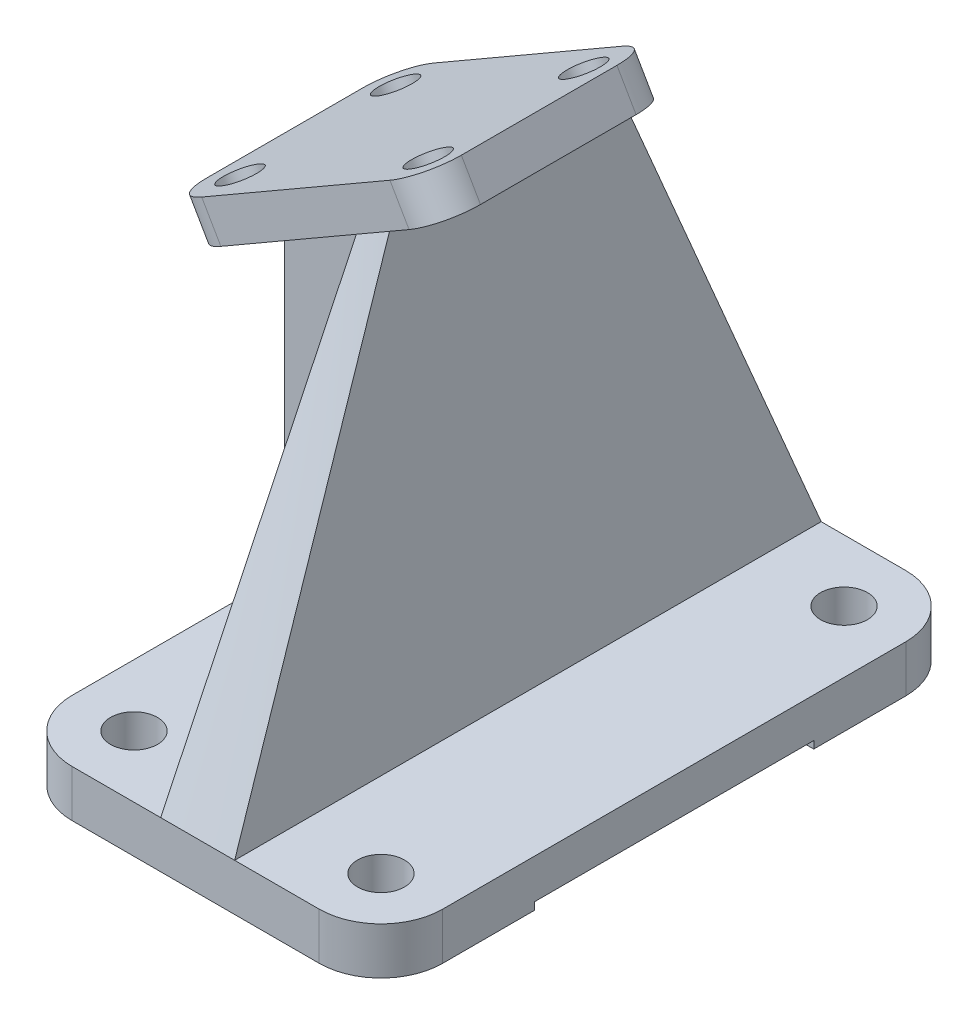
SolidWorks part; units mm, degrees
material "PA Type 6"
ref_plane "Front Plane" through (0, 0, 0) normal (0, 0, 1) x (1, 0, 0)
ref_plane "Top Plane" through (0, 0, 0) normal (0, 1, 0) x (1, 0, 0)
ref_plane "Right Plane" through (0, 0, 0) normal (1, 0, 0) x (0, 0, -1)
sketch "Sketch1" plane through (0, 0, 0) normal (0, 1, 0) x (1, 0, 0)
  line L1 (-25.4, 60.325) -> (25.4, 60.325)
  line L2 (-38.1, 47.625) -> (-38.1, -47.625)
  line L3 (-25.4, -60.325) -> (25.4, -60.325)
  line L4 (38.1, 47.625) -> (38.1, -47.625)
  arc A0 (-25.4, 60.325) -> (-38.1, 47.625) centre (-25.4, 47.625) ccw
  arc A1 (25.4, 60.325) -> (38.1, 47.625) centre (25.4, 47.625) cw
  arc A2 (25.4, -60.325) -> (38.1, -47.625) centre (25.4, -47.625) ccw
  arc A3 (-38.1, -47.625) -> (-25.4, -60.325) centre (-25.4, -47.625) ccw
  circle A4 centre (-25.4, -47.625) radius 4.826
  circle A5 centre (25.4, -47.625) radius 4.826
  circle A6 centre (25.4, 47.625) radius 4.826
  circle A7 centre (-25.4, 47.625) radius 4.826
  point P0 (0, 0)
  point P1 (0, 0)
  point P2 (0, -60.325)
  point P3 (38.1, 0)
  point P22 (0, 0)
  point P23 (0, 0)
  dimension "D3" = 12.7
  dimension "D4" = 9.652
  dimension "D1" = 95.25
  dimension "D2" = 76.2
extrude "Boss-Extrude1" add sketch "Sketch1" along normal blind 9.652
sketch "Sketch2" plane through (-38.1, 0, 0) normal (-1, 0, 0) x (0, 0, 1)
  line L1 (-28.702, 1.524) -> (28.702, 1.524)
  line L2 (-28.702, 1.524) -> (-28.702, -1.524)
  line L3 (-28.702, -1.524) -> (28.702, -1.524)
  line L4 (28.702, 1.524) -> (28.702, -1.524)
  line L5 (-28.702, 1.524) -> (28.702, -1.524) construction
  line L6 (-28.702, -1.524) -> (28.702, 1.524) construction
  point P0 (0, 0)
  point P6 (0, 0)
  point P7 (28.702, 0)
  dimension "D1" = 3.048
  dimension "D2" = 57.404
extrude "Cut-Extrude1" cut sketch "Sketch2" against normal through all
sketch "Sketch3" plane through (0, 9.652, 0) normal (0, 1, 0) x (1, 0, 0)
  line L0 (0, 60.325) -> (0, -60.325) construction
  line L1 (25.4, 60.325) -> (-25.4, 60.325) construction
  line L2 (-25.4, -60.325) -> (25.4, -60.325) construction
  line L3 (-38.1, 47.625) -> (-38.1, -47.625) construction
  line L4 (8.0051, 60.325) -> (-7.2117, 60.325)
  line L5 (8.0051, 60.325) -> (8.0051, -60.325)
  line L6 (8.0051, -60.325) -> (-7.2117, -60.325)
  line L7 (-7.2117, 60.325) -> (-7.2117, -60.325)
  circle A0 centre (-25.4, -47.625) radius 4.826 construction
  point P12 (0, 0)
  point P14 (-33.4581, -42.6977)
  dimension "D2" = 25.4
  dimension "D1" = 17.526
sketch "Sketch4" plane through (0, 0, 0) normal (0, 0, 1) x (1, 0, 0)
  line L0 (-38.1, 9.652) -> (-38.1, 77.216) construction
  line L1 (-38.1, 77.216) -> (4.1761, 101.6241) construction
  point P2 (0, 0)
  point P5 (0, 0)
  dimension "D1" = 67.564
  dimension "D2" = 120
ref_plane "Plane1" through (-42.9605, 74.4098, 0) normal (0.5, -0.866, 0) x (0.866, 0.5, 0)
sketch "Sketch5" plane through (-42.9605, 74.4098, 0) normal (0.5, -0.866, 0) x (0.866, 0.5, 0)
  line L1 (5.6124, -23.876) -> (66.0644, -23.876)
  line L2 (5.6124, -23.876) -> (5.6124, 23.876)
  line L3 (5.6124, 23.876) -> (66.0644, 23.876)
  line L4 (66.0644, -23.876) -> (66.0644, 23.876)
  line L5 (5.6124, 0) -> (66.0644, 0) construction
  line L7 (5.6124, 0) -> (54.4286, 0) construction
  point P7 (0, 0)
  point P8 (5.6124, 0)
  dimension "D1" = 60.452
  dimension "D2" = 47.752
extrude "Boss-Extrude2" add sketch "Sketch5" against normal blind 7.874 separate body
fillet "Fillet1" radius 7.874 4 edges at (-40.0685, 80.6255, -23.876) (12.2845, 110.8515, -23.876) (12.2845, 110.8515, 23.876) (-40.0685, 80.6255, 23.876)
sketch "Sketch7" plane through (-46.8975, 81.2289, 0) normal (-0.5, 0.866, 0) x (0.866, 0.5, 0)
  circle A0 centre (13.4864, 16.002) radius 3.937
  circle A1 centre (13.4864, -16.002) radius 3.937
  circle A2 centre (58.1904, -16.002) radius 3.937
  circle A3 centre (58.1904, 16.002) radius 3.937
  dimension "D1" = 7.874
extrude "Cut-Extrude2" cut sketch "Sketch7" against normal up to surface (7.874 mm away) up to face at (-11.9235, 92.329, 0)
sketch "Sketch9" plane through (0, 0, 0) normal (1, 0, 0) x (0, 0, -1)
  line L0 (-60.325, 9.652) -> (-23.876, 99.213) construction
  point P3 (0, 0)
sketch "Sketch10" plane through (-42.9605, 74.4098, 0) normal (0.5, -0.866, 0) x (0.866, 0.5, 0)
  line L0 (58.1904, 23.876) -> (13.4864, 23.876) construction
  line L1 (53.5435, 23.876) -> (45.6695, 23.876)
  line L2 (53.5435, 23.876) -> (53.5435, -23.876)
  line L3 (53.5435, -23.876) -> (45.6695, -23.876)
  line L4 (45.6695, 23.876) -> (45.6695, -23.876)
  line L5 (13.4864, -23.876) -> (58.1904, -23.876) construction
  point P8 (49.6065, 23.876)
  dimension "D1" = 7.874
loft "Loft1" add profiles "Sketch3", "Sketch10"
sketch "Sketch11" plane through (0, 0, 0) normal (0, 0, 1) x (1, 0, 0)
  line L0 (-38.1, 9.652) -> (-38.1, 77.216) construction
  line L1 (-38.1, 9.652) -> (-38.1, 77.216)
rib "Rib1" sketch "Sketch11" sketch "Sketch11" thickness 7.874 extrusion direction parallel to sketch draft on no parameters "D1"=7.874
